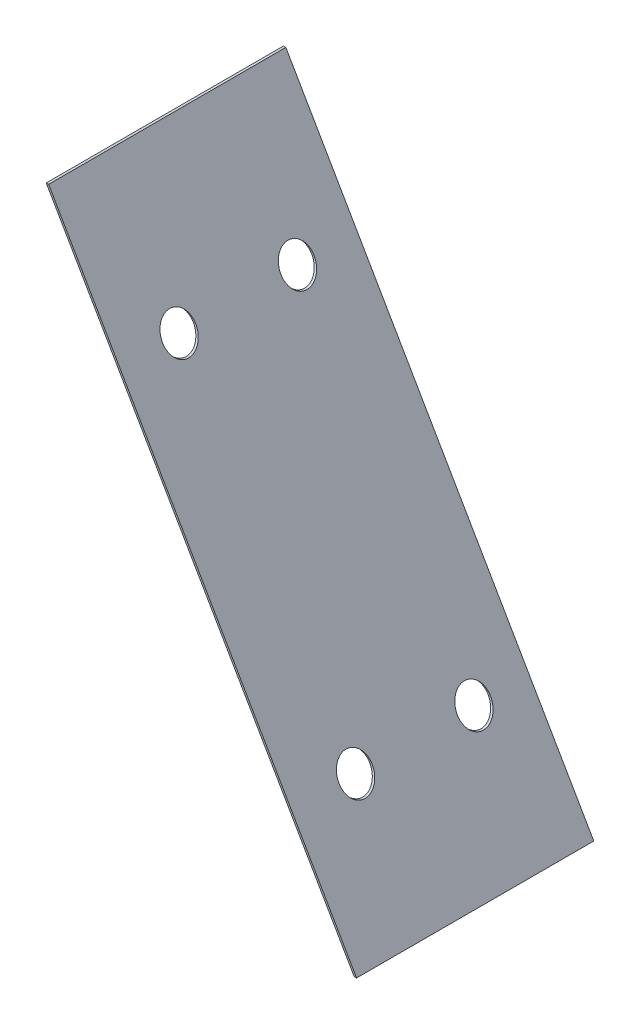
SolidWorks part; units mm, degrees
ref_plane "Front Plane" through (0, 0, 0) normal (0, 0, 1) x (1, 0, 0)
ref_plane "Top Plane" through (0, 0, 0) normal (0, 1, 0) x (1, 0, 0)
ref_plane "Right Plane" through (0, 0, 0) normal (1, 0, 0) x (0, 0, -1)
sketch "Sketch1" plane through (0, 0, 0) normal (0, 0, 1) x (1, 0, 0)
  line L0 (0, 0) -> (0.254, 0)
  line L1 (0.254, 0) -> (32.773, -56.3244)
  line L2 (32.773, -56.3244) -> (32.5189, -56.3244)
  line L3 (32.5189, -56.3244) -> (0, 0)
extrude "Boss-Extrude1" add sketch "Sketch1" against normal up to surface (25.05 mm away)
sketch "Sketch3" plane through (-4.876, 0, 0) normal (-1, 0, 0) x (0, 0, 1)
  circle A0 centre (-18.775, -13) radius 1.75
  circle A1 centre (-6.275, -13) radius 1.75
  circle A2 centre (-18.775, -13) radius 1.75 construction
  circle A3 centre (-6.275, -13) radius 1.75 construction
extrude "Cut-Extrude1" cut sketch "Sketch3" against normal through all
sketch "Sketch4" plane through (37.649, 0, 0) normal (1, 0, 0) x (0, 0, -1)
  circle A0 centre (6.75, -44.4494) radius 1.75
  circle A1 centre (19.25, -44.4494) radius 1.75
  circle A2 centre (6.75, -44.4494) radius 1.75 construction
  circle A3 centre (19.25, -44.4494) radius 1.75 construction
extrude "Cut-Extrude2" cut sketch "Sketch4" against normal through all
